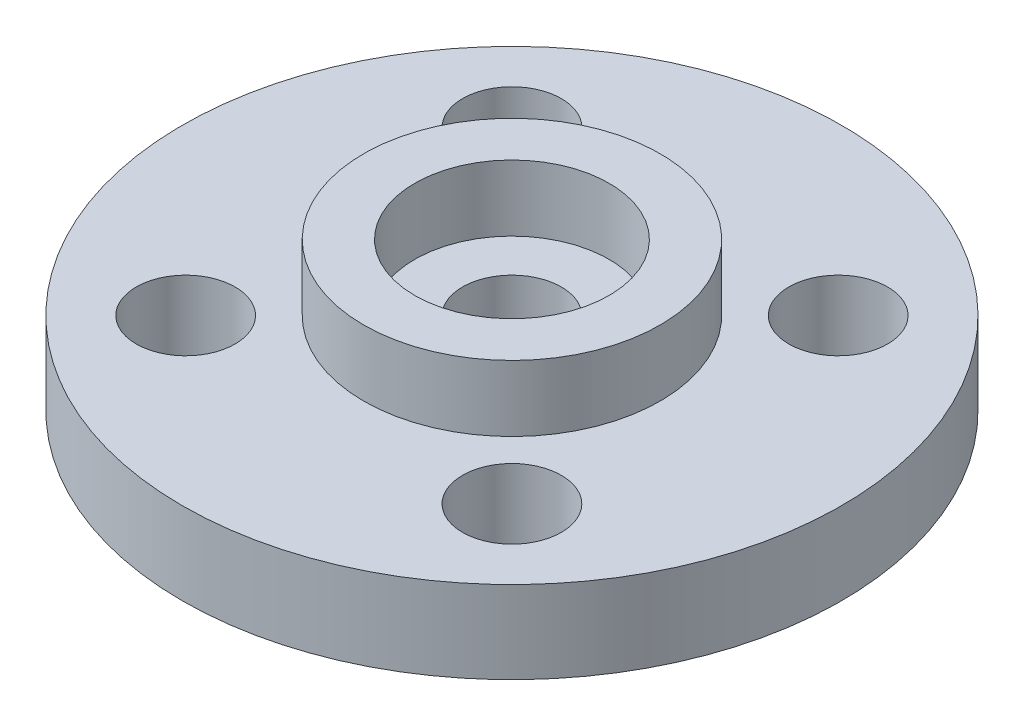
SolidWorks part; units mm, degrees
ref_plane "前视基准面" through (0, 0, 0) normal (0, 0, 1) x (1, 0, 0)
ref_plane "上视基准面" through (0, 0, 0) normal (0, 1, 0) x (1, 0, 0)
ref_plane "右视基准面" through (0, 0, 0) normal (1, 0, 0) x (0, 0, -1)
sketch "草图1" plane through (0, 0, 0) normal (0, 1, 0) x (1, 0, 0)
  line L1 (4.9497, 4.9497) -> (-4.9497, 4.9497) construction
  line L2 (4.9497, 4.9497) -> (4.9497, -4.9497) construction
  line L3 (4.9497, -4.9497) -> (-4.9497, -4.9497) construction
  line L4 (-4.9497, 4.9497) -> (-4.9497, -4.9497) construction
  line L5 (4.9497, 4.9497) -> (-4.9497, -4.9497) construction
  line L6 (4.9497, -4.9497) -> (-4.9497, 4.9497) construction
  circle A0 centre (0, 0) radius 10
  circle A1 centre (-4.9497, 4.9497) radius 1.5
  circle A2 centre (-4.9497, -4.9497) radius 1.5
  circle A3 centre (4.9497, -4.9497) radius 1.5
  circle A4 centre (0, 0) radius 1.5
  circle A5 centre (4.9497, 4.9497) radius 1.5
  dimension "D1" = 20
  dimension "D3" = 3
  dimension "D2" = 14
extrude "凸台-拉伸1" add sketch "草图1" along normal blind 2.5
sketch "草图2" plane through (0, 2.5, 0) normal (0, 1, 0) x (1, 0, 0)
  circle A0 centre (0, 0) radius 4.5
  circle A1 centre (0, 0) radius 2.95
  dimension "D1" = 9
  dimension "D2" = 5.9
extrude "凸台-拉伸2" add sketch "草图2" along normal blind 2
